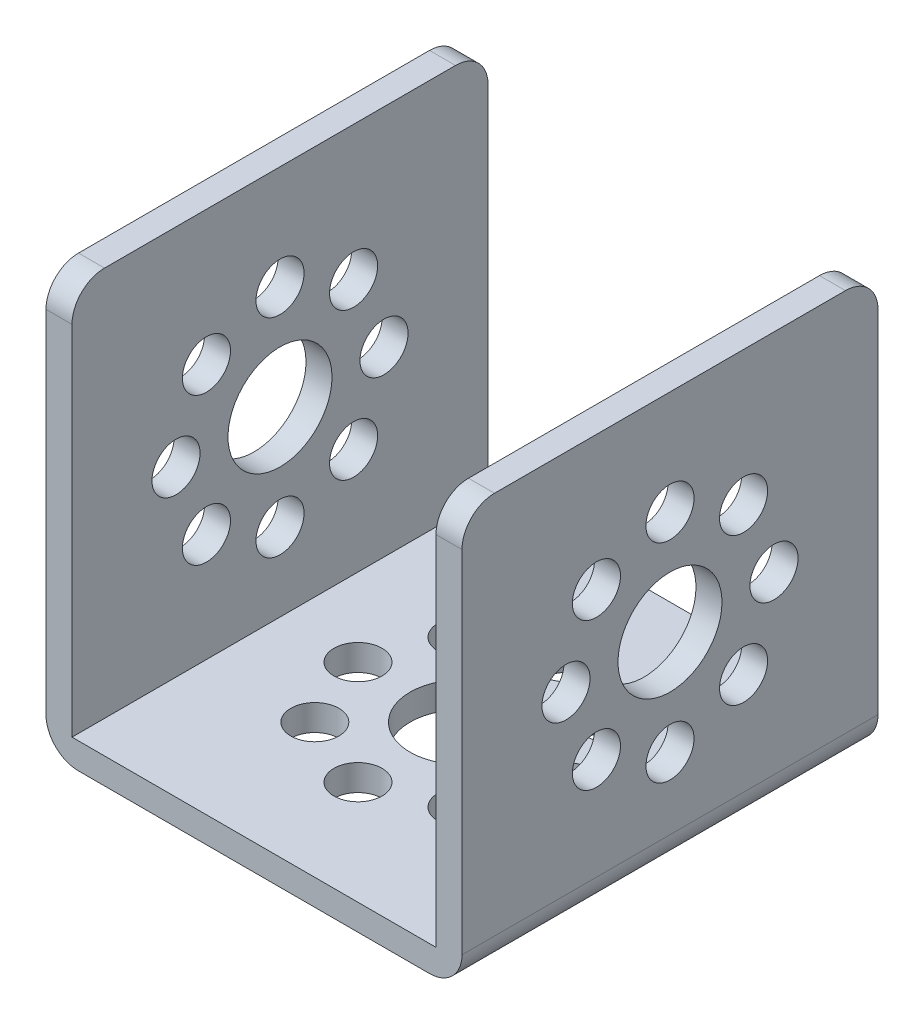
SolidWorks part; units mm, degrees
material "5052 Alloy"
ref_plane "Front Plane" through (0, 0, 0) normal (0, 0, 1) x (1, 0, 0)
ref_plane "Top Plane" through (0, 0, 0) normal (0, 1, 0) x (1, 0, 0)
ref_plane "Right Plane" through (0, 0, 0) normal (1, 0, 0) x (0, 0, -1)
sketch "Sketch3" plane through (0, 0, 0) normal (0, 0, 1) x (1, 0, 0)
  line L0 (2.5, 0) -> (29.5, 0)
  line L1 (32, 2.5) -> (32, 32)
  line L2 (32, 32) -> (30, 32)
  line L3 (30, 32) -> (30, 2)
  line L4 (30, 2) -> (2, 2)
  line L5 (2, 2) -> (2, 32)
  line L6 (2, 32) -> (0, 32)
  line L7 (0, 32) -> (0, 2.5)
  arc A0 (32, 2.5) -> (29.5, 0) centre (29.5, 2.5) cw
  arc A1 (0, 2.5) -> (2.5, 0) centre (2.5, 2.5) ccw
  point P11 (32, 0)
  point P14 (0, 0)
  dimension "D7" = 2.5
  dimension "D8" = 2.5
  dimension "D1" = 2
  dimension "D2" = 2
  dimension "D3" = 32
  dimension "D4" = 32
  dimension "D5" = 32
  dimension "D6" = 30
extrude "Extrude1" add sketch "Sketch3" along normal blind 32
fillet "Fillet1" radius 2.5 1 edges at (31, 32, 32)
fillet "Fillet2" radius 2.5 1 edges at (1, 32, 32)
fillet "Fillet3" radius 2.5 1 edges at (1, 32, 0)
fillet "Fillet4" radius 2.5 1 edges at (31, 32, 0)
sketch "Sketch5" plane through (32, 0, 0) normal (1, 0, 0) x (0, 0, -1)
  line L0 (-29.5, 32) -> (-2.5, 32) construction
  circle A0 centre (-16, 16) radius 4
  circle A1 centre (-16, 8) radius 1.85
  circle A2 centre (-16, 24) radius 1.85
  circle A3 centre (-24, 16) radius 1.85
  circle A4 centre (-8, 16) radius 1.85
  circle A5 centre (-10.34, 21.66) radius 1.85
  circle A6 centre (-21.66, 21.66) radius 1.85
  circle A7 centre (-10.34, 10.34) radius 1.85
  circle A8 centre (-21.66, 10.34) radius 1.85
  arc A9 (-29.5, 32) -> (-32, 29.5) centre (-29.5, 29.5) ccw construction
  point P2 (-16, 32)
  dimension "D1" = 8
  dimension "D6" = 3.7
  dimension "D7" = 3.7
  dimension "D9" = 3.7
  dimension "D11" = 3.7
  dimension "D12" = 3.7
  dimension "D16" = 3.7
  dimension "D18" = 3.7
  dimension "D19" = 3.7
  dimension "D2" = 16
  dimension "D3" = 16
  dimension "D4" = 8
  dimension "D5" = 8
  dimension "D8" = 8
  dimension "D10" = 8
  dimension "D13" = 5.66
  dimension "D14" = 5.66
  dimension "D15" = 5.66
  dimension "D17" = 5.66
  dimension "D20" = 5.66
  dimension "D21" = 5.66
extrude "Cut-Extrude1" cut sketch "Sketch5" against normal blind 32
sketch "Sketch8" plane through (0, 2, 0) normal (0, 1, 0) x (1, 0, 0)
  circle A0 centre (16, -16) radius 4
  circle A1 centre (24, -16) radius 1.85
  circle A2 centre (8, -16) radius 1.85
  circle A3 centre (16, -8) radius 1.85
  circle A4 centre (16, -24) radius 1.85
  circle A5 centre (21.66, -10.34) radius 1.85
  circle A6 centre (21.66, -21.66) radius 1.85
  circle A7 centre (10.34, -21.66) radius 1.85
  circle A8 centre (10.34, -10.34) radius 1.85
  dimension "D1" = 8
  dimension "D4" = 3.7
  dimension "D5" = 3.7
  dimension "D6" = 3.7
  dimension "D7" = 3.7
  dimension "D12" = 3.7
  dimension "D13" = 3.7
  dimension "D14" = 3.7
  dimension "D15" = 3.7
  dimension "D2" = 16
  dimension "D3" = 14
  dimension "D8" = 8
  dimension "D9" = 8
  dimension "D10" = 8
  dimension "D11" = 8
  dimension "D16" = 5.66
  dimension "D17" = 5.66
  dimension "D18" = 5.66
  dimension "D19" = 5.66
  dimension "D20" = 5.66
  dimension "D21" = 5.66
  dimension "D22" = 5.66
  dimension "D23" = 5.66
extrude "Cut-Extrude2" cut sketch "Sketch8" against normal blind 2
